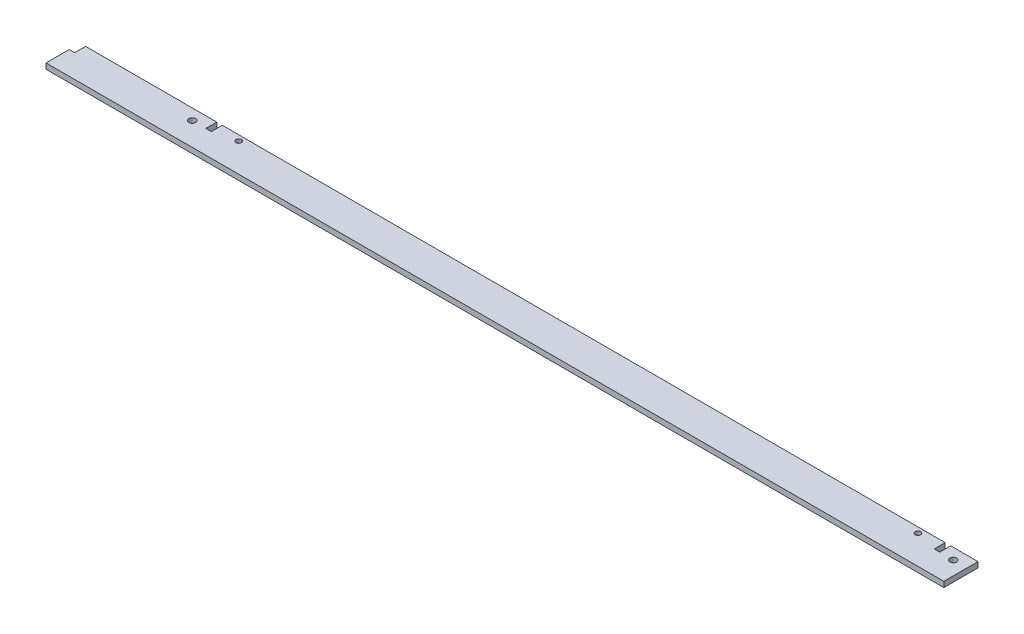
SolidWorks part; units mm, degrees
material "Beech"
ref_plane "Front Plane" through (0, 0, 0) normal (0, 0, 1) x (1, 0, 0)
ref_plane "Top Plane" through (0, 0, 0) normal (0, 1, 0) x (1, 0, 0)
ref_plane "Right Plane" through (0, 0, 0) normal (1, 0, 0) x (0, 0, -1)
sketch "Sketch2" plane through (0, 0, 0) normal (0, 1, 0) x (1, 0, 0)
  line L0 (-362.4387, -81.105) -> (-262.4387, -81.105)
  line L2 (-362.4387, -81.105) -> (-362.4387, -106.105)
  line L3 (-362.4387, -106.105) -> (294.5613, -106.105)
  line L4 (294.5613, -81.105) -> (294.5613, -106.105)
  line L9 (-262.4387, -81.105) -> (-262.4387, -89.105)
  line L10 (-262.4387, -89.105) -> (-258.4387, -89.105)
  line L11 (-258.4387, -89.105) -> (-258.4387, -81.105)
  line L12 (-258.4387, -81.105) -> (270.5613, -81.105)
  line L13 (270.5613, -81.105) -> (270.5613, -89.105)
  line L14 (270.5613, -89.105) -> (274.5613, -89.105)
  line L15 (274.5613, -89.105) -> (274.5613, -81.105)
  line L16 (274.5613, -81.105) -> (294.5613, -81.105)
  circle A0 centre (284.5613, -89.105) radius 2.5
  circle A1 centre (-272.4387, -89.105) radius 2.5
  circle A4 centre (254.5613, -85.105) radius 2
  circle A5 centre (-242.4387, -85.105) radius 2
  dimension "D4" = 5
  dimension "D6" = 5
  dimension "D12" = 4
  dimension "D21" = 4
  dimension "D1" = 657
  dimension "D2" = 25
  dimension "D3" = 10
  dimension "D5" = 17
  dimension "D7" = 90
  dimension "D8" = 16
  dimension "D9" = 17
  dimension "D13" = 40
  dimension "D14" = 21
  dimension "D15" = 20
  dimension "D16" = 4
  dimension "D17" = 8
  dimension "D18" = 100
  dimension "D19" = 4
  dimension "D20" = 8
  dimension "D22" = 120
  dimension "D23" = 21
extrude "Boss-Extrude2" add sketch "Sketch2" along normal blind 4
sketch "Sketch3" plane through (0, 4, 0) normal (0, 1, 0) x (1, 0, 0)
  line L6 (-362.4387, -81.105) -> (-358.4387, -81.105)
  line L7 (-362.4387, -81.105) -> (-362.4387, -89.105)
  line L8 (-362.4387, -89.105) -> (-358.4387, -89.105)
  line L9 (-358.4387, -81.105) -> (-358.4387, -89.105)
  dimension "D1" = 8
  dimension "D2" = 4
extrude "Cut-Extrude1" cut sketch "Sketch3" against normal blind 4
